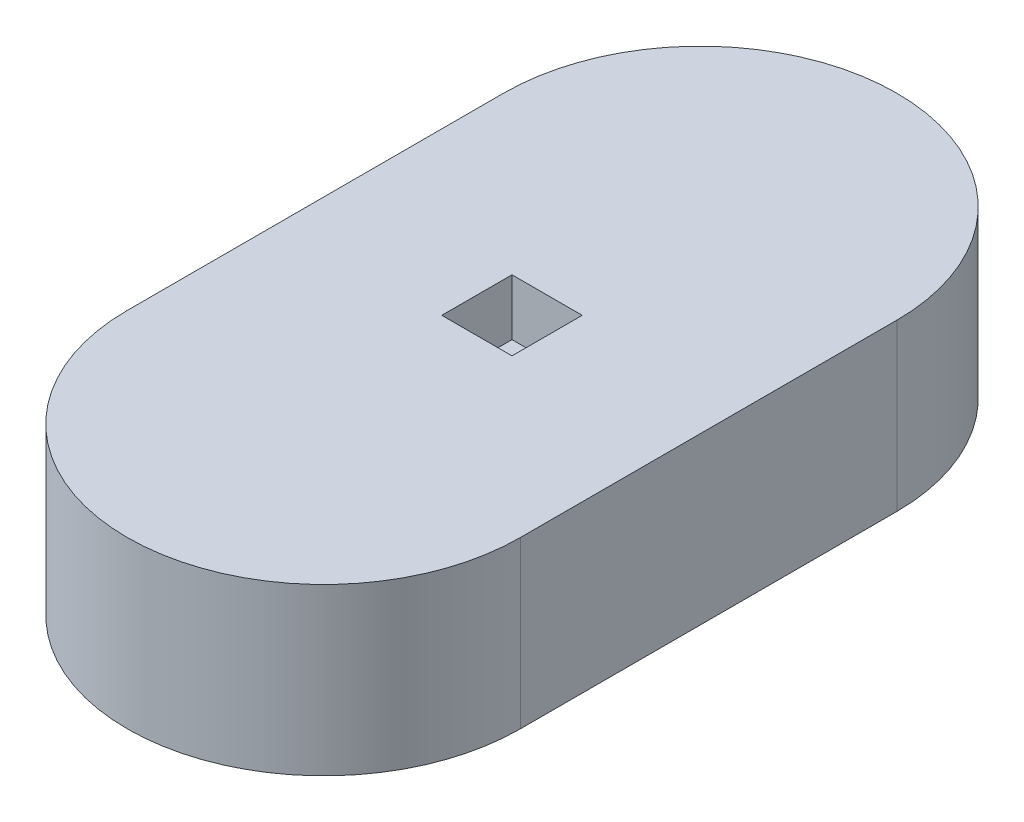
SolidWorks part; units mm, degrees
ref_plane "Front Plane" through (0, 0, 0) normal (0, 0, 1) x (1, 0, 0)
ref_plane "Top Plane" through (0, 0, 0) normal (0, 1, 0) x (1, 0, 0)
ref_plane "Right Plane" through (0, 0, 0) normal (1, 0, 0) x (0, 0, -1)
sketch "Sketch1" plane through (0, 0, 0) normal (0, 1, 0) x (1, 0, 0)
  line L0 (0, 0) -> (0, 13.4) construction
  line L1 (-7, 0) -> (-7, 13.4)
  line L2 (7, 0) -> (7, 13.4)
  arc A0 (-7, 0) -> (7, 0) centre (0, 0) ccw
  arc A1 (7, 13.4) -> (-7, 13.4) centre (0, 13.4) ccw
  point P3 (0, 6.7)
  dimension "D1" = 14
  dimension "D2" = 13.4
extrude "Boss-Extrude1" add sketch "Sketch1" along normal blind 5.9
sketch "Sketch2" plane through (0, 5.9, 0) normal (0, 1, 0) x (1, 0, 0)
  line L0 (-7, 13.4) -> (-7, 0) construction
  line L1 (-1.25, 5.45) -> (1.25, 5.45)
  line L2 (-1.25, 5.45) -> (-1.25, 7.95)
  line L3 (-1.25, 7.95) -> (1.25, 7.95)
  line L4 (1.25, 5.45) -> (1.25, 7.95)
  dimension "D1" = 2.5
  dimension "D2" = 2.5
  dimension "D3" = 5.75
  dimension "D4" = 5.45
extrude "Cut-Extrude1" cut sketch "Sketch2" against normal blind 2
